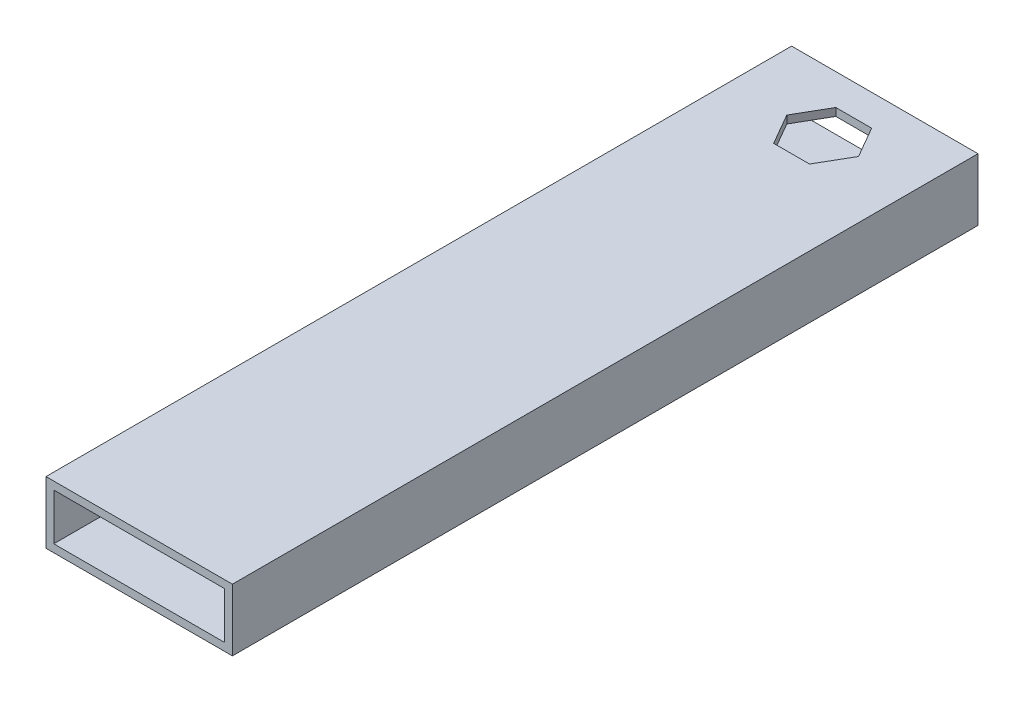
SolidWorks part; units mm, degrees
material "6061 Alloy"
ref_plane "Front Plane" through (0, 0, 0) normal (0, 0, 1) x (1, 0, 0)
ref_plane "Top Plane" through (0, 0, 0) normal (0, 1, 0) x (1, 0, 0)
ref_plane "Right Plane" through (0, 0, 0) normal (1, 0, 0) x (0, 0, -1)
sketch "Sketch1" plane through (0, 0, 0) normal (0, 0, 1) x (1, 0, 0)
  line L1 (0, 0) -> (38.1, 0)
  line L2 (0, 0) -> (0, 12.7)
  line L3 (0, 12.7) -> (38.1, 12.7)
  line L4 (38.1, 0) -> (38.1, 12.7)
  dimension "D1" = 38.1
  dimension "D2" = 12.7
extrude "Boss-Extrude1" add sketch "Sketch1" along normal blind 152.4
sketch "Sketch2" plane through (0, 0, 152.4) normal (0, 0, 1) x (1, 0, 0)
  line L4 (36.5125, 1.5875) -> (36.5125, 11.1125)
  line L5 (36.5125, 1.5875) -> (36.5125, 11.1125)
  line L6 (1.5875, 11.1125) -> (1.5875, 1.5875)
  line L7 (1.5875, 11.1125) -> (1.5875, 1.5875)
  line L8 (36.5125, 11.1125) -> (1.5875, 11.1125)
  line L9 (1.5875, 1.5875) -> (36.5125, 1.5875)
  line L10 (36.5125, 11.1125) -> (1.5875, 11.1125)
  line L13 (1.5875, 1.5875) -> (36.5125, 1.5875)
  dimension "D1" = 1.5875
extrude "Cut-Extrude1" cut sketch "Sketch2" against normal through all
sketch "Sketch3" plane through (0, 0, 0) normal (0, -1, 0) x (1, 0, 0)
  line L3 (26.3823, 12.7) -> (22.7162, 19.05)
  line L4 (22.7162, 19.05) -> (15.3838, 19.05)
  line L5 (15.3838, 19.05) -> (11.7177, 12.7)
  line L6 (11.7177, 12.7) -> (15.3838, 6.35)
  line L7 (15.3838, 6.35) -> (22.7162, 6.35)
  line L8 (22.7162, 6.35) -> (26.3823, 12.7)
  line L9 (38.1, 152.4) -> (38.1, 0) construction
  line L10 (0, 0) -> (38.1, 0) construction
  circle A0 centre (19.05, 12.7) radius 6.35 construction
  dimension "D3" = 12.7
  dimension "D1" = 12.7
  dimension "D2" = 19.05
extrude "Cut-Extrude2" cut sketch "Sketch3" against normal through all
